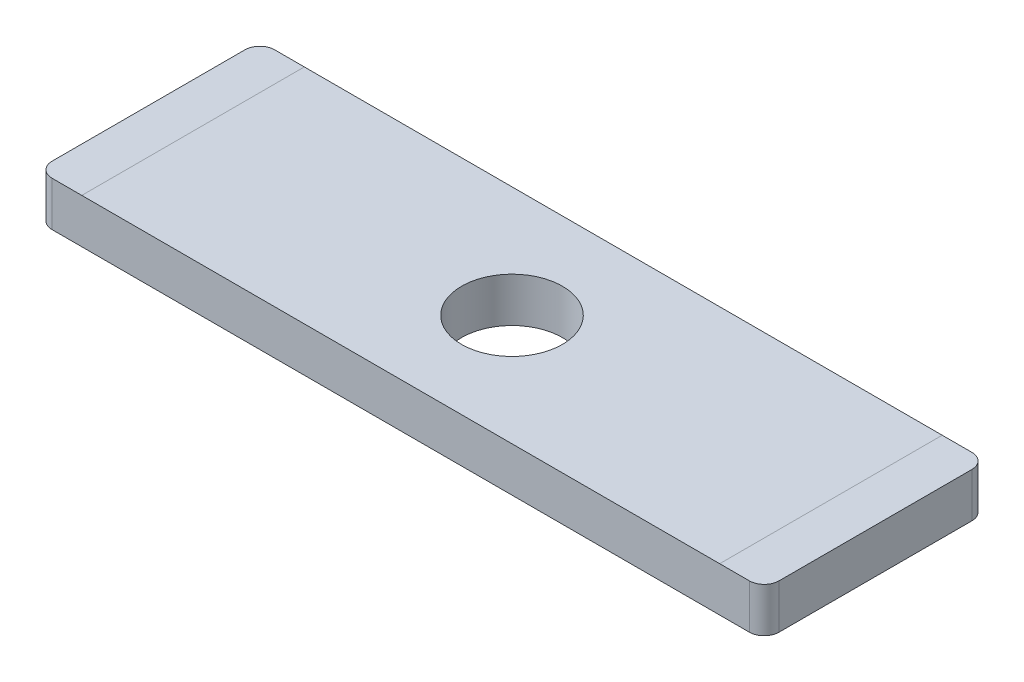
SolidWorks part; units mm, degrees
ref_plane "Front Plane" through (0, 0, 0) normal (0, 0, 1) x (1, 0, 0)
ref_plane "Top Plane" through (0, 0, 0) normal (0, 1, 0) x (1, 0, 0)
ref_plane "Right Plane" through (0, 0, 0) normal (1, 0, 0) x (0, 0, -1)
sketch "Sketch1" plane through (0, 0, 0) normal (0, 1, 0) x (1, 0, 0)
  line L0 (-24.5, 7.5) -> (24.5, -7.5) construction
  line L1 (-24.5, 7.5) -> (24.5, 7.5)
  line L2 (-24.5, 7.5) -> (-24.5, -7.5)
  line L3 (-24.5, -7.5) -> (24.5, -7.5)
  line L4 (24.5, 7.5) -> (24.5, -7.5)
  point P4 (0, 0)
  dimension "D1" = 15
  dimension "D2" = 49
extrude "Boss-Extrude1" add sketch "Sketch1" along normal blind 3
sketch "Sketch2" plane through (0, 3, 0) normal (0, 1, 0) x (1, 0, 0)
  circle A0 centre (0, 0) radius 3.4
  dimension "D1" = 6.8
extrude "Cut-Extrude1" cut sketch "Sketch2" against normal through all
fillet "Fillet1" radius 1 4 edges at (24.5, 1.5, -7.5) (24.5, 1.5, 7.5) (-24.5, 1.5, -7.5) (-24.5, 1.5, 7.5)
sketch "Sketch3" plane through (0, 3, 0) normal (0, 1, 0) x (1, 0, 0)
  line L0 (-24.5, 6.5) -> (-24.5, -6.5) construction
  line L1 (-25.8748, 8.0683) -> (-21.5, 8.0683)
  line L2 (-25.8748, 8.0683) -> (-25.8748, -9.2875)
  line L3 (-25.8748, -9.2875) -> (-21.5, -9.2875)
  line L4 (-21.5, 8.0683) -> (-21.5, -9.2875)
  line L5 (25.7111, 8.0683) -> (21.5, 8.0683)
  line L6 (25.7111, 8.0683) -> (25.7111, -8.4628)
  line L7 (25.7111, -8.4628) -> (21.5, -8.4628)
  line L8 (21.5, 8.0683) -> (21.5, -8.4628)
  line L9 (24.5, -6.5) -> (24.5, 6.5) construction
  dimension "D1" = 3
  dimension "D2" = 3
split line "Split Line1"
